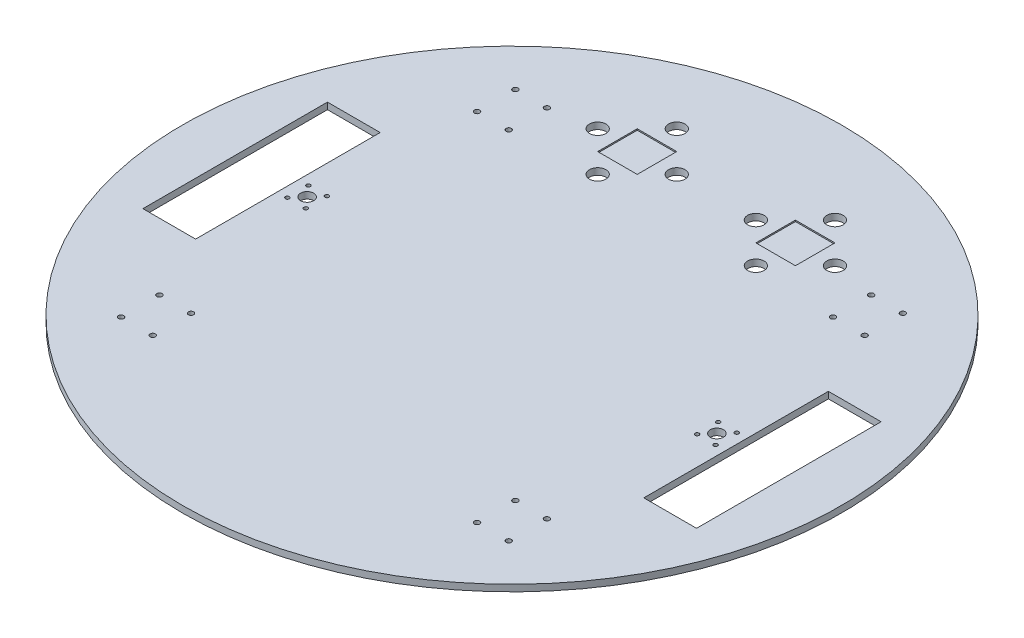
SolidWorks part; units mm, degrees
ref_plane "Front Plane" through (0, 0, 0) normal (0, 0, 1) x (1, 0, 0)
ref_plane "Top Plane" through (0, 0, 0) normal (0, 1, 0) x (1, 0, 0)
ref_plane "Right Plane" through (0, 0, 0) normal (1, 0, 0) x (0, 0, -1)
sketch "Sketch1" plane through (0, 0, 0) normal (0, 1, 0) x (1, 0, 0)
  line L0 (-250, 0) -> (250, 0)
  circle A0 centre (0, 0) radius 250
  dimension "D1" = 500
extrude "Boss-Extrude1_cicle body" add sketch "Sketch1" along normal blind 5 contours A0
sketch "Sketch2" plane through (0, 0, 0) normal (0, 1, 0) x (1, 0, 0)
  line L0 (0, 250) -> (0, -250) construction
  line L1 (-141.0592, -141.7826) -> (141.0592, -141.7826)
  line L2 (-141.0592, -141.7826) -> (-141.0592, 141.7826)
  line L3 (-141.0592, 141.7826) -> (141.0592, 141.7826)
  line L4 (141.0592, -141.7826) -> (141.0592, 141.7826)
  line L5 (-141.0592, -141.7826) -> (141.0592, 141.7826) construction
  line L6 (-141.0592, 141.7826) -> (141.0592, -141.7826) construction
  circle A0 centre (0, 0) radius 200 construction
  circle A1 centre (0, 0) radius 250 construction
  dimension "D1" = 283.5652
  dimension "D2" = 400
  dimension "D3" = 282.1184
sketch "Sketch3" plane through (0, 0, 0) normal (0, 1, 0) x (1, 0, 0)
  line L1 (-161.0592, 121.7826) -> (-121.0592, 121.7826)
  line L2 (-161.0592, 121.7826) -> (-161.0592, 161.7826)
  line L3 (-161.0592, 161.7826) -> (-121.0592, 161.7826)
  line L4 (-121.0592, 121.7826) -> (-121.0592, 161.7826)
  line L5 (-161.0592, 121.7826) -> (-121.0592, 161.7826) construction
  line L6 (-161.0592, 161.7826) -> (-121.0592, 121.7826) construction
  line L18 (-210, -70) -> (-210, 70)
  line L19 (-141.0592, 141.7826) -> (141.0592, 141.7826) construction
  line L20 (-366.0402, 0) -> (388.3561, 0) construction
  line L21 (0, -161.7826) -> (0, 180) construction
  line L22 (170, -70) -> (210, -70)
  line L23 (170, -70) -> (170, 70)
  line L24 (170, 70) -> (210, 70)
  line L25 (210, -70) -> (210, 70)
  line L26 (170, -70) -> (210, 70) construction
  line L27 (170, 70) -> (210, -70) construction
  line L28 (-170, -70) -> (-170, 70)
  line L29 (-210, 70) -> (-170, 70)
  line L30 (-210, -70) -> (-170, -70)
  line L31 (-141.0592, 141.7826) -> (141.0592, -141.7826) construction
  line L32 (0, 180) -> (0, 250) construction
  line L33 (-251.1491, 180) -> (448.8509, 180) construction
  line L34 (141.0592, -141.7826) -> (200, -141.7826) construction
  line L35 (100, 315.1379) -> (100, -284.8621) construction
  line L36 (-100, 269.2203) -> (-100, -330.7797) construction
  circle A0 centre (0, 0) radius 150
  circle A1 centre (0, 0) radius 250 construction
  point P0 (-141.0592, 141.7826)
  point P6 (190, 0)
  point P20 (0, 215)
  point P23 (0, 0)
  dimension "D8" = 2
  dimension "D10" = 300
  dimension "D2" = 180
  dimension "D1" = 40
  dimension "D3" = 40
  dimension "D4" = 20
  dimension "D5" = 140
  dimension "D6" = 40
  dimension "D7" = 170
  dimension "D9" = 340
  dimension "D11" = 100
  dimension "D12" = 100
  dimension "D13" = 600
  dimension "D14" = 600
  dimension "D15" = 700
  dimension "D16" = 70
extrude "Cut-drive wheel" cut sketch "Sketch3" against normal mid plane 100 contours L18 L29 L28 L30 | L23 L22 L25 L24
sketch "Sketch5" plane through (0, 5, 0) normal (0, 1, 0) x (1, 0, 0)
  line L0 (-250, 0) -> (250, 0) construction
  line L1 (-162.4063, -8) -> (-146.4418, -8) construction
  line L2 (-167, -13.25) -> (-143.8125, -13.25) construction
  line L3 (-167, -13.25) -> (-167, 13.25) construction
  line L4 (-167, 13.25) -> (-143.8125, 13.25)
  line L5 (-143.8125, -13.25) -> (-143.8125, 13.25) construction
  line L6 (-167, -13.25) -> (-143.8125, 13.25) construction
  line L7 (-167, 13.25) -> (-143.8125, -13.25) construction
  line L8 (-170, -70) -> (-170, 70) construction
  circle A0 centre (0, 0) radius 250 construction
  circle A1 centre (-155.4063, 0) radius 5
  circle A2 centre (-148.4063, 8) radius 1.5
  circle A3 centre (-148.4063, -8) radius 1.5
  circle A4 centre (-162.4063, 8) radius 1.5
  circle A5 centre (-162.4063, -8) radius 1.5
  point P5 (-155.4063, 0)
  dimension "D4" = 2
  dimension "D7" = 10
  dimension "D10" = 3
  dimension "D1" = 26.5
  dimension "D2" = 7
  dimension "D3" = 3
  dimension "D6" = 7
  dimension "D8" = 8
  dimension "D9" = 16
  dimension "D11" = 7
  dimension "D12" = 7
  dimension "D5" = 2
extrude "Cut- drive wheel_fixation" cut sketch "Sketch5" against normal blind 10 contours A5 | A2 | A1 | A3 | A4
mirror "Mirror-drive wheel" about plane through (0, 0, 0) normal (1, 0, 0) of "Cut- drive wheel_fixation"
sketch "Sketch6" plane through (0, 5, 0) normal (0, 1, 0) x (1, 0, 0)
  line L6 (-147, 149.5) -> (-123, 149.5) construction
  line L8 (-123, 149.5) -> (-123, 120.5) construction
  line L9 (-123, 120.5) -> (-147, 120.5) construction
  line L10 (-147, 120.5) -> (-147, 149.5) construction
  line L11 (0, 250) -> (0, -250) construction
  line L12 (-250, 0) -> (250, 0) construction
  line L13 (-135, 149.5) -> (-135, 120.5) construction
  line L14 (-147, 135) -> (-123, 135) construction
  circle A0 centre (-123, 149.5) radius 2
  circle A1 centre (-147, 149.5) radius 2
  circle A2 centre (-147, 120.5) radius 2
  circle A3 centre (-123, 120.5) radius 2
  circle A17 centre (0, 0) radius 250 construction
  circle A18 centre (123, 149.5) radius 2
  circle A19 centre (147, 149.5) radius 2
  circle A20 centre (147, 120.5) radius 2
  circle A21 centre (123, 120.5) radius 2
  circle A22 centre (123, -149.5) radius 2
  circle A23 centre (123, -120.5) radius 2
  circle A24 centre (147, -149.5) radius 2
  circle A25 centre (147, -120.5) radius 2
  circle A26 centre (-123, -120.5) radius 2
  circle A27 centre (-147, -120.5) radius 2
  circle A28 centre (-147, -149.5) radius 2
  circle A29 centre (-123, -149.5) radius 2
  dimension "D3" = 4
  dimension "D5" = 24
  dimension "D6" = 4
  dimension "D1" = 29
  dimension "D2" = 135
  dimension "D9" = 135
  dimension "D4" = 2
  dimension "D7" = 2
extrude "Cut-Extrude_caster_wheeel_cut" cut sketch "Sketch6" against normal blind 10
sketch "Sketch7" plane through (0, 5, 0) normal (0, 1, 0) x (1, 0, 0)
  line L0 (0, 250) -> (0, -250) construction
  line L1 (-250, 0) -> (250, 0) construction
  line L2 (-60, 263.2806) -> (-60, -249.8499) construction
  line L3 (75, 140) -> (45, 140)
  line L4 (-75, 140) -> (-45, 140)
  line L5 (-75, 140) -> (-75, 170)
  line L6 (-75, 170) -> (-45, 170)
  line L7 (-45, 140) -> (-45, 170)
  line L8 (-75, 140) -> (-45, 170) construction
  line L9 (-75, 170) -> (-45, 140) construction
  line L10 (75, 140) -> (75, 170)
  line L11 (75, 170) -> (45, 170)
  line L12 (45, 140) -> (45, 170)
  line L13 (60, 170) -> (60, 140) construction
  line L14 (-151.9319, 155) -> (113.3019, 155) construction
  line L17 (-110, 169) -> (-75, 169) construction
  line L18 (-110, 169) -> (-110, 141) construction
  line L19 (-110, 141) -> (-75, 141) construction
  line L20 (-75, 169) -> (-75, 141) construction
  line L21 (35, 95) -> (-465, 95) construction
  line L22 (-120, 60) -> (-120, 560) construction
  line L24 (-155, 215) -> (345, 215) construction
  circle A0 centre (0, 0) radius 250 construction
  circle A1 centre (-90, 155) radius 6.25
  circle A2 centre (-60, 185) radius 6.25
  circle A3 centre (-30, 155) radius 6.25
  circle A4 centre (-60, 125) radius 6.25
  circle A5 centre (90, 155) radius 6.25
  circle A6 centre (60, 125) radius 6.25
  circle A7 centre (30, 155) radius 6.25
  circle A8 centre (60, 185) radius 6.25
  point P11 (-60, 155)
  point P43 (-60, 155)
  dimension "D13" = 12.5
  dimension "D19" = 14
  dimension "D2" = 30
  dimension "D3" = 30
  dimension "D4" = 140
  dimension "D5" = 30
  dimension "D6" = 30
  dimension "D7" = 60
  dimension "D8" = 60
  dimension "D9" = 140
  dimension "D10" = 28
  dimension "D11" = 35
  dimension "D12" = 14
  dimension "D14" = 15
  dimension "D15" = 45
  dimension "D17" = 60
  dimension "D18" = 30
  dimension "D20" = 155
  dimension "D16" = 4
extrude "Cut-Extrude__extrusion_fixation_base" cut sketch "Sketch7" against normal blind 1
sketch "Sketch9" plane through (0, 4, 0) normal (0, 1, 0) x (1, 0, 0)
  circle A0 centre (-60, 185) radius 6.25 construction
  circle A1 centre (-60, 185) radius 6.25
  circle A2 centre (-30, 155) radius 6.25 construction
  circle A3 centre (-30, 155) radius 6.25
  circle A4 centre (-60, 125) radius 6.25 construction
  circle A5 centre (-90, 155) radius 6.25
  circle A6 centre (-90, 155) radius 6.25
  circle A7 centre (-60, 125) radius 6.25
  circle A9 centre (60, 185) radius 6.25
  circle A10 centre (60, 185) radius 6.25
  circle A11 centre (30, 155) radius 6.25
  circle A12 centre (30, 155) radius 6.25
  circle A13 centre (60, 125) radius 6.25
  circle A14 centre (60, 125) radius 6.25
  circle A15 centre (90, 155) radius 6.25
  circle A16 centre (90, 155) radius 6.25
  dimension "D1" = 0
  dimension "D2" = 0
  dimension "D3" = 0
  dimension "D4" = 0
  dimension "D5" = 0
extrude "Cut-Extrude_1.25 bracket holes" cut sketch "Sketch9" against normal blind 71
